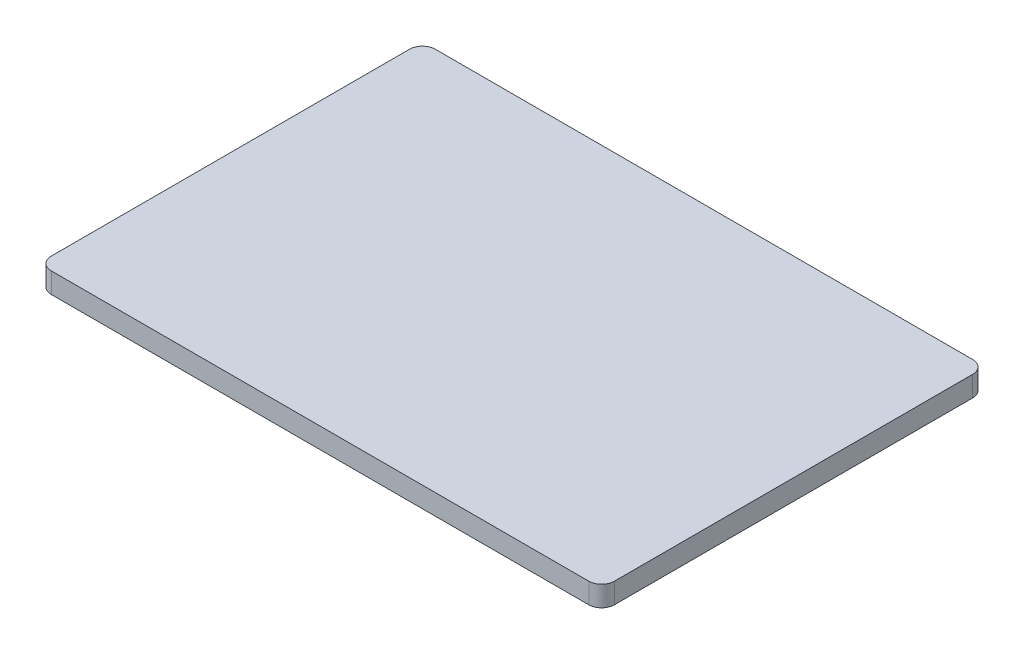
SolidWorks part; units mm, degrees
ref_plane "Front Plane" through (0, 0, 0) normal (0, 0, 1) x (1, 0, 0)
ref_plane "Top Plane" through (0, 0, 0) normal (0, 1, 0) x (1, 0, 0)
ref_plane "Right Plane" through (0, 0, 0) normal (1, 0, 0) x (0, 0, -1)
sketch "Sketch1" plane through (0, 0, 0) normal (0, 1, 0) x (1, 0, 0)
  line L1 (-110, -75) -> (110, -75)
  line L2 (-110, -75) -> (-110, 75)
  line L3 (-110, 75) -> (110, 75)
  line L4 (110, -75) -> (110, 75)
  line L5 (-110, -75) -> (110, 75) construction
  line L6 (-110, 75) -> (110, -75) construction
  point P0 (0, 0)
  dimension "D1" = 150
  dimension "D2" = 220
extrude "Boss-Extrude1" add sketch "Sketch1" along normal mid plane 8
fillet "Fillet1" radius 5 4 edges at (110, 0, -75) (-110, 0, -75) (-110, 0, 75) (110, 0, 75)
